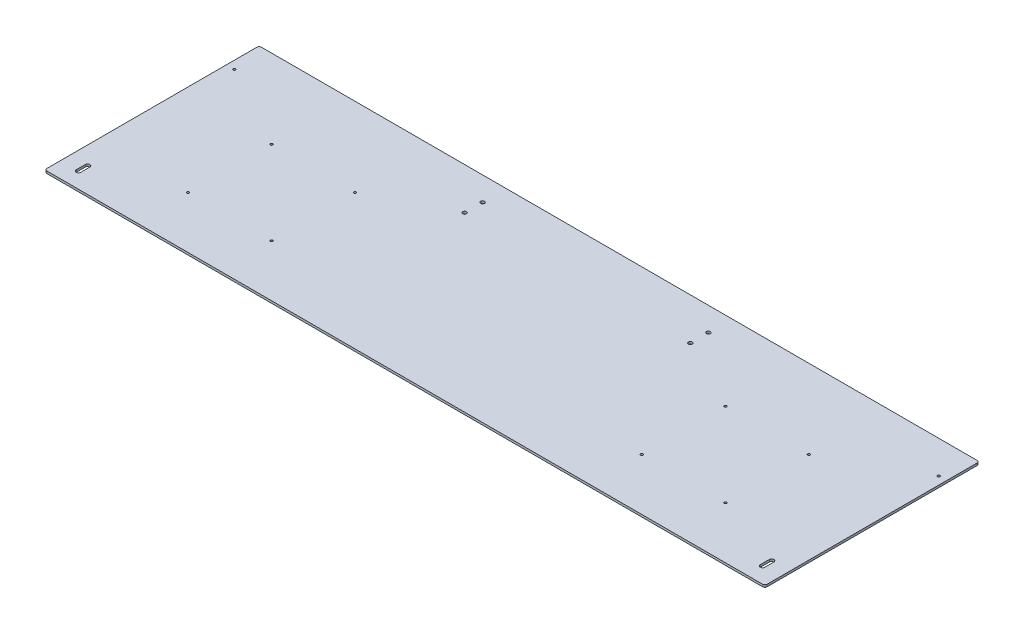
SolidWorks part; units mm, degrees
material "PC High Viscosity"
ref_plane "Front Plane" through (0, 0, 0) normal (0, 0, 1) x (1, 0, 0)
ref_plane "Top Plane" through (0, 0, 0) normal (0, 1, 0) x (1, 0, 0)
ref_plane "Right Plane" through (0, 0, 0) normal (1, 0, 0) x (0, 0, -1)
sketch "Sketch1" plane through (0, 0, 0) normal (0, 1, 0) x (1, 0, 0)
  line L0 (695.325, 485.775) -> (1330.325, 485.775) construction
  line L1 (6.35, 0) -> (2019.3, 0)
  line L2 (0, 6.35) -> (0, 596.9)
  line L3 (6.35, 603.25) -> (2019.3, 603.25)
  line L4 (2025.65, 6.35) -> (2025.65, 596.9)
  line L5 (50.8, 69.85) -> (50.8, 44.45) construction
  line L6 (257.175, 381) -> (492.125, 381) construction
  line L7 (257.175, 381) -> (257.175, 146.05) construction
  line L8 (1012.825, 603.25) -> (1012.825, 0) construction
  line L9 (57.15, 69.85) -> (57.15, 44.45)
  line L10 (44.45, 69.85) -> (44.45, 44.45)
  line L11 (1974.85, 69.85) -> (1974.85, 44.45) construction
  line L12 (1968.5, 69.85) -> (1968.5, 44.45)
  line L13 (1981.2, 69.85) -> (1981.2, 44.45)
  line L14 (695.325, 485.775) -> (695.325, 536.575) construction
  arc A0 (2019.3, 603.25) -> (2025.65, 596.9) centre (2019.3, 596.9) cw
  arc A1 (2019.3, 0) -> (2025.65, 6.35) centre (2019.3, 6.35) ccw
  arc A2 (6.35, 0) -> (0, 6.35) centre (6.35, 6.35) cw
  arc A3 (0, 596.9) -> (6.35, 603.25) centre (6.35, 596.9) cw
  circle A4 centre (695.325, 485.775) radius 5.3578
  circle A8 centre (1330.325, 485.775) radius 5.3578
  circle A17 centre (257.175, 381) radius 3.3782
  circle A18 centre (492.125, 381) radius 3.3782
  circle A19 centre (492.125, 146.05) radius 3.3782
  circle A20 centre (257.175, 146.05) radius 3.3782
  circle A23 centre (1330.325, 53.975) radius 5.3578 [skipped]
  circle A24 centre (695.325, 536.575) radius 5.3578
  arc A25 (57.15, 69.85) -> (44.45, 69.85) centre (50.8, 69.85) ccw
  circle A26 centre (1768.475, 146.05) radius 3.3782
  circle A27 centre (1533.525, 146.05) radius 3.3782
  circle A28 centre (1533.525, 381) radius 3.3782
  circle A29 centre (1768.475, 381) radius 3.3782
  circle A30 centre (22.225, 511.175) radius 3.3734
  circle A31 centre (2003.425, 511.175) radius 3.3734
  circle A32 centre (695.325, 53.975) radius 5.3578 [skipped]
  arc A33 (44.45, 44.45) -> (57.15, 44.45) centre (50.8, 44.45) ccw
  arc A34 (1968.5, 69.85) -> (1981.2, 69.85) centre (1974.85, 69.85) cw
  arc A35 (1981.2, 44.45) -> (1968.5, 44.45) centre (1974.85, 44.45) cw
  circle A36 centre (1330.325, 536.575) radius 5.3578
  point P7 (2025.65, 603.25)
  point P12 (0, 0)
  point P15 (0, 603.25)
  point P26 (50.8, 57.15)
  point P58 (1974.85, 57.15)
  dimension "D3" = 6.35
  dimension "D6" = 10.7156
  dimension "D12" = 222.25
  dimension "D13" = 6.7564
  dimension "D19" = 234.95
  dimension "D20" = 92.075
  dimension "D22" = 6.7469
  dimension "D11" = 6.35
  dimension "D25" = 2
  dimension "D1" = 2025.65
  dimension "D2" = 603.25
  dimension "D4" = 117.475
  dimension "D5" = 695.325
  dimension "D9" = 50.8
  dimension "D10" = 635
  dimension "D14" = 257.175
  dimension "D17" = 90
  dimension "D18" = 234.95
  dimension "D21" = 22.225
  dimension "D23" = 25.4
  dimension "D24" = 546.1
  dimension "D26" = 50.8
  dimension "D7" = 2
  dimension "D8" = 2
  dimension "D15" = 2
  dimension "D16" = 2
extrude "Boss-Extrude1" add sketch "Sketch1" along normal blind 6.35
